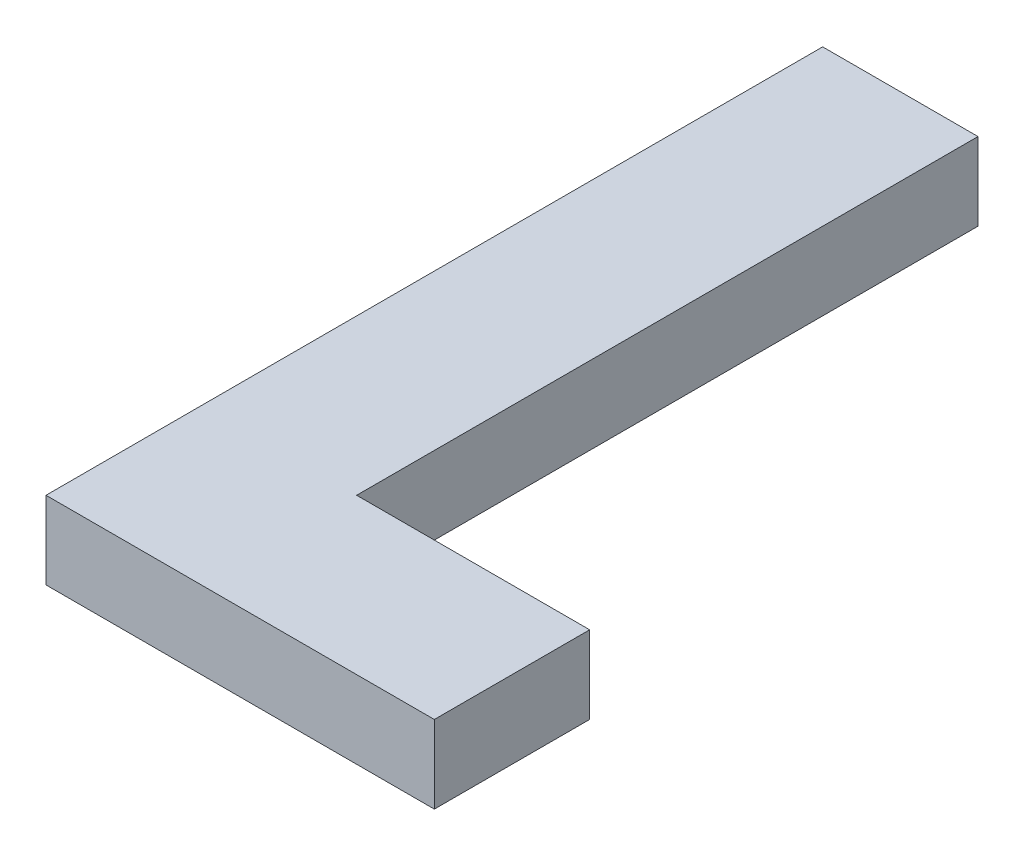
SolidWorks part; units mm, degrees
ref_plane "Front Plane" through (0, 0, 0) normal (0, 0, 1) x (1, 0, 0)
ref_plane "Top Plane" through (0, 0, 0) normal (0, 1, 0) x (1, 0, 0)
ref_plane "Right Plane" through (0, 0, 0) normal (1, 0, 0) x (0, 0, -1)
sketch "Sketch1" plane through (0, 0, 0) normal (0, 1, 0) x (1, 0, 0)
  line L1 (-10, 40) -> (10, 40)
  line L2 (-10, 40) -> (-10, -40)
  line L3 (-10, -40) -> (10, -40)
  line L4 (10, 40) -> (10, -40)
  point P0 (0, 0)
  dimension "D1" = 10
  dimension "D2" = 10
  dimension "D3" = 40
  dimension "D4" = 40
extrude "Boss-Extrude1" add sketch "Sketch1" along normal blind 10
sketch "Sketch3" plane through (0, 10, 0) normal (0, 1, 0) x (1, 0, 0)
  line L0 (-10, -40) -> (40, -40)
  line L1 (40, -40) -> (40, -60)
  line L2 (40, -60) -> (-10, -60)
  line L3 (-10, -60) -> (-10, -40)
  line L4 (10, -40) -> (10, 40) construction
  dimension "D1" = 30
  dimension "D2" = 20
  dimension "D3" = 80
  dimension "D4" = 100
extrude "Boss-Extrude2" add sketch "Sketch3" against normal blind 10
